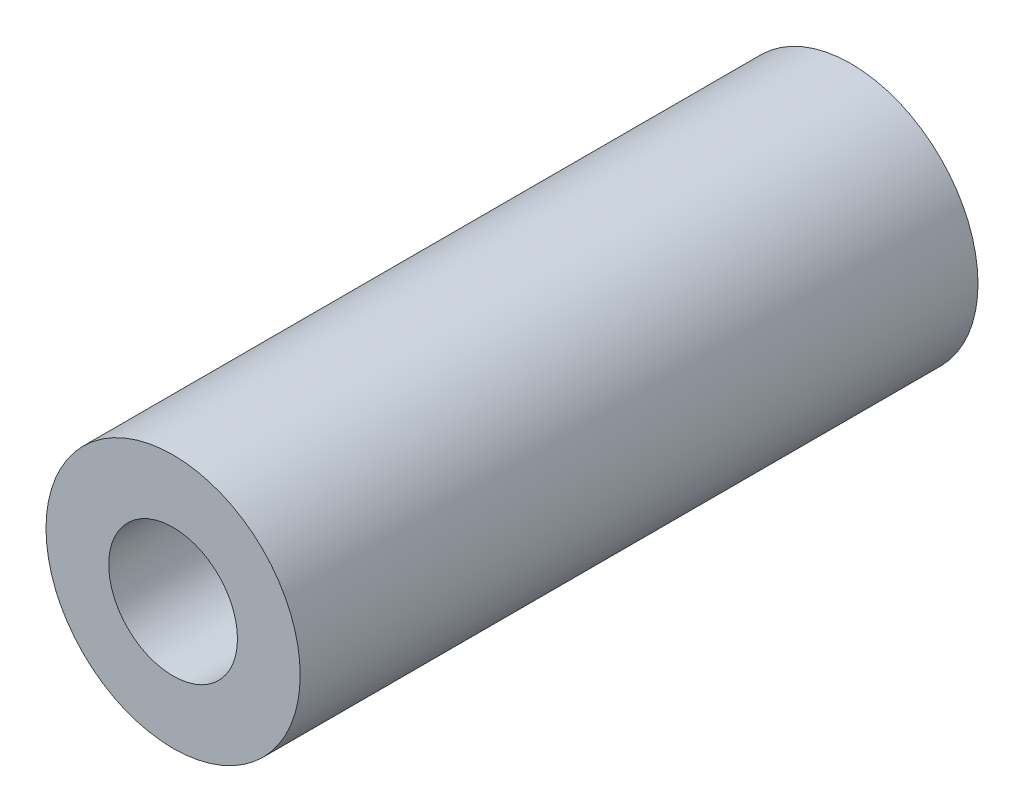
SolidWorks part; units mm, degrees
ref_plane "Front Plane" through (0, 0, 0) normal (0, 0, 1) x (1, 0, 0)
ref_plane "Top Plane" through (0, 0, 0) normal (0, 1, 0) x (1, 0, 0)
ref_plane "Right Plane" through (0, 0, 0) normal (1, 0, 0) x (0, 0, -1)
sketch "Sketch1" plane through (0, 0, 0) normal (0, 0, 1) x (1, 0, 0)
  circle A0 centre (0, 0) radius 4.826
  circle A1 centre (0, 0) radius 9.525
  dimension "D1" = 19.05
  dimension "D2" = 9.652
extrude "Boss-Extrude1" add sketch "Sketch1" along normal blind 50.8
